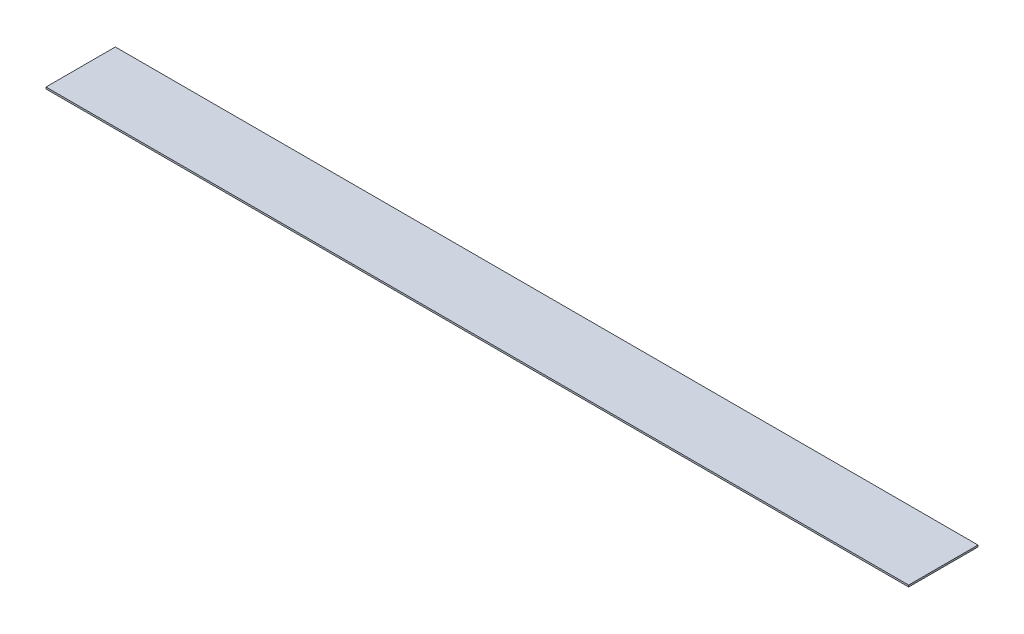
SolidWorks part; units mm, degrees
material "Acrylic (Medium-high impact)"
ref_plane "Front Plane" through (0, 0, 0) normal (0, 0, 1) x (1, 0, 0)
ref_plane "Top Plane" through (0, 0, 0) normal (0, 1, 0) x (1, 0, 0)
ref_plane "Right Plane" through (0, 0, 0) normal (1, 0, 0) x (0, 0, -1)
sketch "Sketch1" plane through (0, 0, 0) normal (0, 1, 0) x (1, 0, 0)
  line L1 (-790, -63.5) -> (790, -63.5) construction
  line L2 (-790, -63.5) -> (-790, 63.5) construction
  line L3 (-790, 63.5) -> (790, 63.5) construction
  line L4 (790, -63.5) -> (790, 63.5) construction
  line L5 (-790, -63.5) -> (790, 63.5) construction
  line L6 (-790, 63.5) -> (790, -63.5) construction
  point P0 (0, 0)
  dimension "Length" = 1580
  dimension "Width" = 127
sketch "Sketch2" plane through (0, 0, 0) normal (1, 0, 0) x (0, 0, -1)
  line L1 (-63.5, -1.5875) -> (63.5, -1.5875) construction
  line L2 (-63.5, -1.5875) -> (-63.5, 1.5875) construction
  line L3 (-63.5, 1.5875) -> (63.5, 1.5875) construction
  line L4 (63.5, -1.5875) -> (63.5, 1.5875) construction
  line L5 (-63.5, -1.5875) -> (63.5, 1.5875) construction
  line L6 (-63.5, 1.5875) -> (63.5, -1.5875) construction
  dimension "Thickness" = 3.175
sketch "Sketch3" plane through (0, 0, 0) normal (1, 0, 0) x (0, 0, -1)
  line L1 (63.5, 1.5875) -> (-63.5, 1.5875)
  line L2 (63.5, 1.5875) -> (63.5, -1.5875)
  line L3 (63.5, -1.5875) -> (-63.5, -1.5875)
  line L4 (-63.5, 1.5875) -> (-63.5, -1.5875)
extrude "Boss-Extrude1" add sketch "Sketch3" against normal up to vertex (790 mm away) and the other way up to vertex (790 mm away) up to point (-790, 0, -63.5) other way up to point (790, 0, -63.5)
